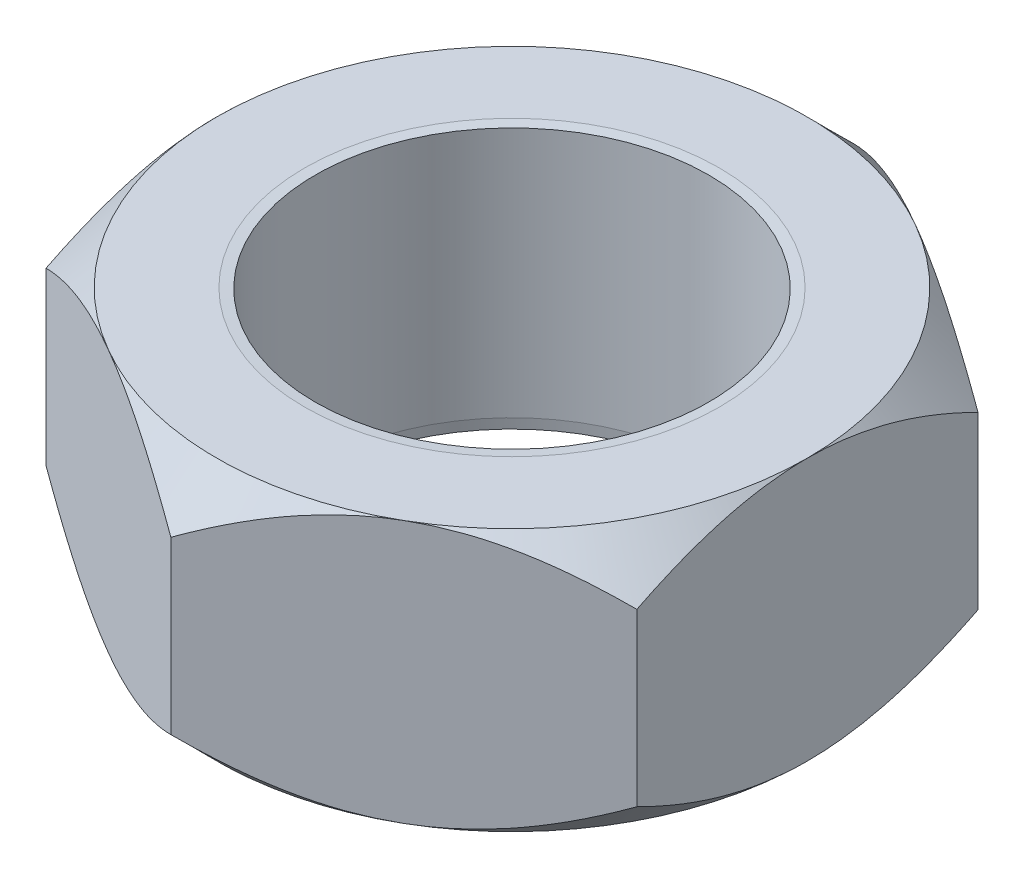
SolidWorks part; units mm, degrees
ref_plane "Front Plane" through (0, 0, 0) normal (0, 0, 1) x (1, 0, 0)
ref_plane "Top Plane" through (0, 0, 0) normal (0, 1, 0) x (1, 0, 0)
ref_plane "Right Plane" through (0, 0, 0) normal (1, 0, 0) x (0, 0, -1)
sketch "Sketch1" plane through (0, 0, 0) normal (0, 1, 0) x (1, 0, 0)
  line L1 (0, 8.2562) -> (-7.1501, 4.1281)
  line L2 (-7.1501, 4.1281) -> (-7.1501, -4.1281)
  line L3 (-7.1501, -4.1281) -> (0, -8.2562)
  line L4 (0, -8.2562) -> (7.1501, -4.1281)
  line L5 (7.1501, -4.1281) -> (7.1501, 4.1281)
  line L6 (7.1501, 4.1281) -> (0, 8.2562)
  circle A0 centre (0, 0) radius 7.1501 construction
  dimension "D1" = 14.3002
extrude "Boss-Extrude1" add sketch "Sketch1" along normal blind 6.35
sketch "Sketch2" plane through (0, 6.35, 0) normal (0, 1, 0) x (1, 0, 0)
  circle A0 centre (0, 0) radius 4.7625
  dimension "D1" = 9.525
extrude "Cut-Extrude1" cut sketch "Sketch2" against normal through all
cosmetic thread "Cosmetic Thread1" parameters "D2"=11.1125
chamfer "Chamfer2" distance 0.254 angle 5 1 edges at (0, 6.35, 4.7625)
chamfer "Chamfer3" distance 0.254 angle 5 1 edges at (0, 0, 4.7625)
sketch "Sketch3" plane through (0, 6.35, 0) normal (0, 1, 0) x (1, 0, 0)
  circle A0 centre (0, 0) radius 7.1501
extrude "Cut-Extrude2" cut sketch "Sketch3" against normal blind 6.35 draft 45 flip side to cut
sketch "Sketch4" plane through (0, 0, 0) normal (0, -1, 0) x (1, 0, 0)
  circle A0 centre (0, 0) radius 7.1501
extrude "Cut-Extrude3" cut sketch "Sketch4" against normal blind 6.35 draft 45 flip side to cut
